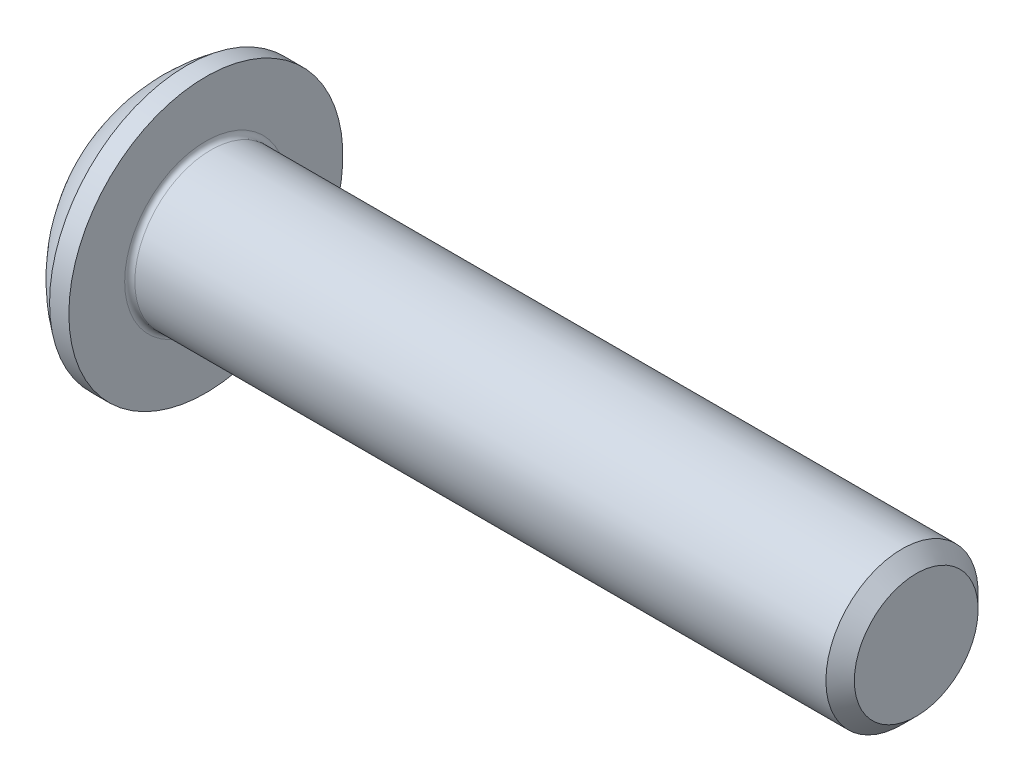
SolidWorks part; units mm, degrees
ref_plane "Plane1" through (0, 0, 0) normal (0, 0, 1) x (1, 0, 0)
ref_plane "Plane2" through (0, 0, 0) normal (0, 1, 0) x (1, 0, 0)
ref_plane "Plane3" through (0, 0, 0) normal (1, 0, 0) x (0, 0, -1)
sketch "BodySke" plane through (0, 0, 0) normal (0, 0, 1) x (1, 0, 0)
  line L0 (15.5, 0) -> (15.5, 1.2195)
  line L1 (15.2195, 1.5) -> (1.5, 1.5)
  line L2 (1.5, 1.5) -> (1.5, 2.7)
  line L3 (1.5, 2.7) -> (1.12, 2.7)
  line L4 (0, 0) -> (101.6, 0) construction
  line L5 (1.5, -2.7) -> (1.12, -2.7) construction
  line L6 (55.6768, -1.5) -> (1.5, -1.5) construction
  line L7 (15.5, 0) -> (0, 0)
  line L8 (0, 1.35) -> (0, -1.35) construction
  line L9 (0, 0) -> (0, 1.35)
  line L10 (15.5, 1.2195) -> (15.2195, 1.5)
  line L11 (15.5, -1.2195) -> (15.2195, -1.5) construction
  line L12 (2, 9.525) -> (2, -1.5) construction
  line L13 (1.5, 9.525) -> (1.5, -1.5) construction
  arc A1 (0, 1.35) -> (1.12, 2.7) centre (3.0008, 0) cw
  dimension "D1" = 2.7
  dimension "Diameter" = 3
  dimension "Length" = 14
  dimension "Head_dia" = 5.4
  dimension "Head_ht" = 1.5
  dimension "Head_side_ht" = 0.38
  dimension "Minor_dia" = 2.439
  dimension "Body_ch_ang" = 45
  dimension "Advance" = 0.5
  dimension "Thread_nom" = 14
revolve "BaseBody" add sketch "BodySke" angle 360 about L4
cosmetic thread "ThreadCosmetic" parameters "Thread_length"=13, "Thread_minor"=2.439
fillet "Fillet1" radius 0.1 1 edges at (1.5, 0, 1.5)
sketch "Sketch2" plane through (0, 0, 0) normal (0, 0, 1) x (1, 0, 0)
  line L0 (0, 1) -> (1.04, 1)
  line L1 (1.04, 1) -> (1.6174, 0)
  line L3 (1.6174, 0) -> (0, 0)
  line L4 (0, 0) -> (0, 1)
  line L5 (0, -1) -> (1.04, -1) construction
  line L6 (0, 0) -> (47.625, 0) construction
  dimension "D2" = 60
  dimension "PreBroach_depth" = 1.04
  dimension "PreBroach_dia" = 2
revolve "PreBroach" cut sketch "Sketch2" angle 360 about L6
sketch "Sketch3" plane through (0, 0, 0) normal (1, 0, 0) x (0, 0, -1)
  line L0 (-1, -0.5774) -> (-1, 0.5774)
  line L1 (-1, 0.5774) -> (0, 1.1547)
  line L2 (0, 1.1547) -> (1, 0.5774)
  line L3 (1, 0.5774) -> (1, -0.5774)
  line L4 (1, -0.5774) -> (0, -1.1547)
  line L5 (0, -1.1547) -> (-1, -0.5774)
  dimension "D1" = 1
  dimension "D2" = 1
  dimension "D3" = 2
  dimension "Hex_size" = 2
extrude "Hex" cut sketch "Sketch3" along normal blind 1.04
sketch "ThdSchSke" plane through (0, 0, 0) normal (0, 0, 1) x (1, 0, 0)
  line L0 (2.5, -1.2195) -> (2.3036, -1.5)
  line L1 (2.5, -1.2195) -> (2.6964, -1.5)
  line L2 (2.6964, -1.5) -> (2.6964, -1.875)
  line L3 (-3.175, 0) -> (5.1513, 0) construction
  line L5 (2.6964, -1.875) -> (2.3036, -1.875)
  line L6 (2.3036, -1.875) -> (2.3036, -1.5)
  dimension "Thread_minor" = 2.439
  dimension "Diameter" = 3
  dimension "Start" = 2.5
  dimension "SideAngle" = 55
  dimension "VeeAngle" = 70
  dimension "Overcut" = 3.75
revolve "ThreadSchematic" [suppressed] cut sketch "ThdSchSke" angle 360 about L3
pattern_linear "ThdSchPat" [suppressed]
equation "\"D1@BodySke\" = \"Head_dia@BodySke\" * .5"
equation "\"Thread_minor@ThreadCosmetic\" = \"Minor_dia@BodySke\""
equation "\"D1@Sketch3\" = \"Hex_size@Sketch3\" / 2"
equation "\"D2@Sketch3\" = \"D1@Sketch3\""
equation "\"D3@Sketch3\" = \"Hex_size@Sketch3\""
equation "\"Thread_length@ThreadCosmetic\" = ((sgn( (\"Length@BodySke\" - \"Advance@BodySke\" * 2.0) - \"Thread_nom@BodySke\" )-1)*( (\"Length@BodySke\" - \"Advance@BodySke\" * 2.0) - \"Thread_nom@BodySke\" ))/-2+ \"Thread_nom@BodySke\""
equation "\"Thread_minor@ThdSchSke\" = \"Minor_dia@BodySke\""
equation "\"Diameter@ThdSchSke\" = \"Diameter@BodySke\""
equation "\"Overcut@ThdSchSke\" = \"Diameter@BodySke\" * 1.25"
equation "\"Start@ThdSchSke\" = \"Head_ht@BodySke\" + \"Length@BodySke\" - \"Thread_length@ThreadCosmetic\"  '---Non-countersunk---"
equation "\"Num_threads@ThdSchPat\" = int( \"Thread_length@ThreadCosmetic\" / \"Advance@BodySke\" + 0.999 )  + 1"
equation "\"Advance@ThdSchPat\" = \"Thread_length@ThreadCosmetic\" /  (\"Num_threads@ThdSchPat\" - 1) 'relax it"
equation "\"Num_threads@ThdSchPat\" = \"Num_threads@ThdSchPat\" - sgn( \"Num_threads@ThdSchPat\" - 1) '---chamfered tips only---"
